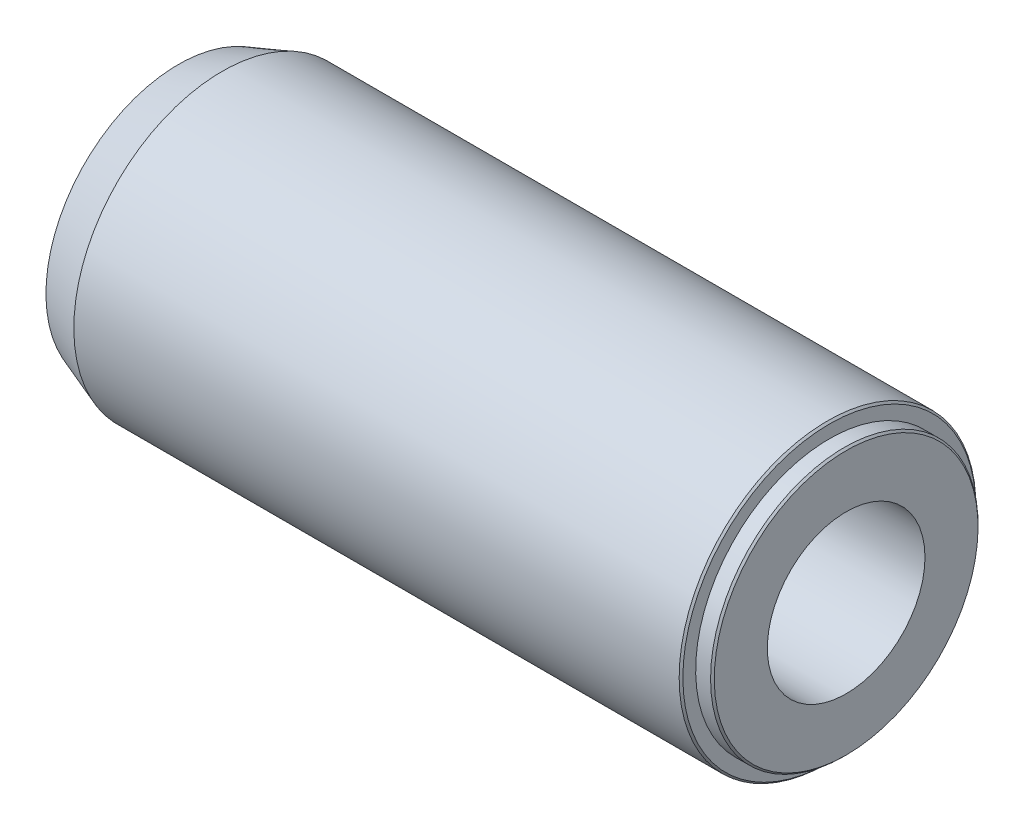
SolidWorks part; units mm, degrees
material "1.0037 (S235JR)"
ref_plane "Alzado" through (0, 0, 0) normal (0, 0, 1) x (1, 0, 0)
ref_plane "Planta" through (0, 0, 0) normal (0, 1, 0) x (1, 0, 0)
ref_plane "Vista lateral" through (0, 0, 0) normal (1, 0, 0) x (0, 0, -1)
sketch "Sketch1" plane through (0, 0, 0) normal (0, 0, 1) x (1, 0, 0)
  line L3 (-3, 7.9972) -> (-35.7343, 7.9972)
  line L25 (-35.7343, 7.9972) -> (-38.0967, 7.1374)
  line L26 (-38.0967, 7.1374) -> (-38.0967, -0.0028)
  line L27 (-3, 7.9972) -> (-3, 7.2075)
  line L34 (-2.0967, 7.2075) -> (-2.0967, -0.0028)
  line L35 (-38.0967, -0.0028) -> (-2.0967, -0.0028)
  line L36 (-2.0967, 7.2075) -> (-3, 7.2075)
  line L39 (-1.4435, 7.2075) -> (-2.75, 7.2075) construction
  dimension "D1" = 8
  dimension "D2" = 20
  dimension "D3" = 7.1402
  dimension "D4" = 36
  dimension "D5" = 7.2102
  dimension "D6" = 0.9033
revolve "Revolve1" add sketch "Sketch1" angle 360 about L35
sketch "Croquis3" plane through (-38.0967, 0, 0) normal (-1, 0, 0) x (0, 0, 1)
  line L1 (0, -3.1568) -> (2.7338, -1.5784)
  line L2 (2.7338, -1.5784) -> (2.7338, 1.5784)
  line L3 (2.7338, 1.5784) -> (0, 3.1568)
  line L4 (0, 3.1568) -> (-2.7338, 1.5784)
  line L5 (-2.7338, 1.5784) -> (-2.7338, -1.5784)
  line L6 (-2.7338, -1.5784) -> (0, -3.1568)
  circle A0 centre (0, 0) radius 2.7338 construction
  dimension "D1" = 3.1568
extrude "Cortar-Extruir1" cut sketch "Croquis3" against normal blind 5
chamfer "Chaflán1" distance 0.1 angle 45 2 edges at (-3, -8.0028, 0) (-2.0967, -7.213, 0)
sketch "Croquis6" plane through (-2.0967, 0, 0) normal (1, 0, 0) x (0, 0, -1)
  circle A0 centre (0, 0) radius 5
  dimension "D1" = 10
hole_wizard "Taladro roscado M101" positions "Croquis10" profile "Croquis9" tap size "M10" standard "DIN"
sketch "Croquis10" plane through (-2.0967, 0, 0) normal (1, 0, 0) x (0, 0, -1)
  point P0 (0, 0)
sketch "Croquis9" plane through (-2.0967, 0, 0) normal (0, 1, 0) x (0, 0, -1)
  line L0 (0, 0) -> (0, 27.5537)
  line L1 (0, 27.5537) -> (4.25, 25)
  line L2 (4.25, 25) -> (4.25, 0)
  line L5 (4.25, 0) -> (0, 0)
  line L10 (0, 27.5537) -> (-4.25, 25) construction
  line L11 (0, -6.35) -> (0, 107.95) construction
  dimension "Diámetro de perforador para roscar" = 8.5
  dimension "Profundidad de perforador para roscar" = 25
  dimension "Ángulo de perforador" = 118
cosmetic thread "Rosca cosmética3" parameters "D1"=23, "D2"=10
